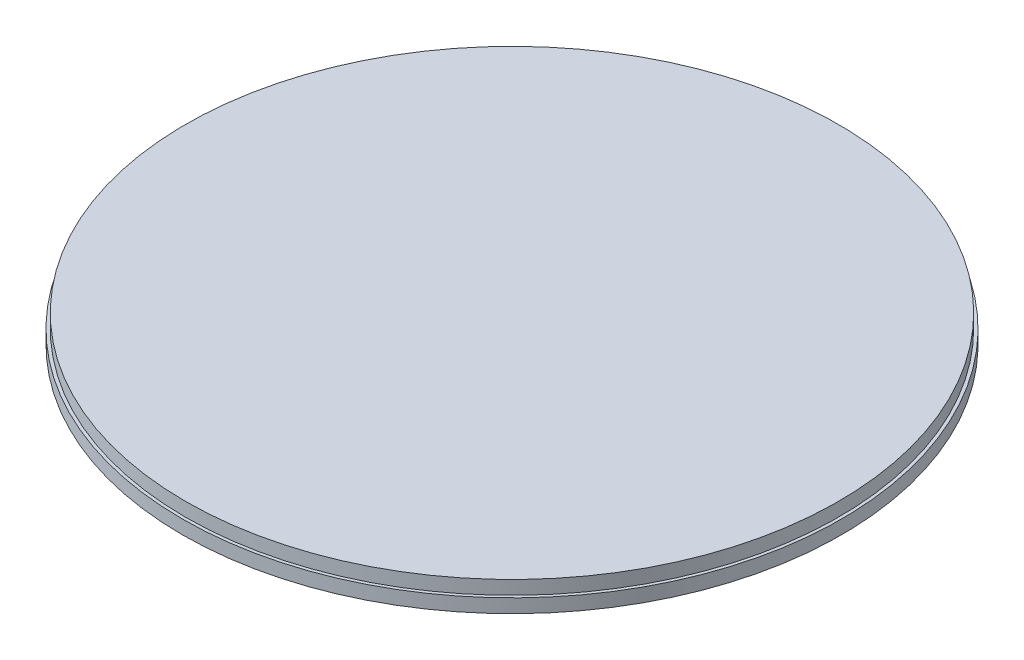
SolidWorks part; units mm, degrees
material "\"G10 fiberglass\""
ref_plane "Front Plane" through (0, 0, 0) normal (0, 0, 1) x (1, 0, 0)
ref_plane "Top Plane" through (0, 0, 0) normal (0, 1, 0) x (1, 0, 0)
ref_plane "Right Plane" through (0, 0, 0) normal (1, 0, 0) x (0, 0, -1)
sketch "Sketch1" plane through (0, 0, 0) normal (0, 1, 0) x (1, 0, 0)
  circle A0 centre (0, 0) radius 76.2
  dimension "D1" = 152.4
extrude "Boss-Extrude1" add sketch "Sketch1" along normal blind 3.175
sketch "Sketch2" plane through (0, 3.175, 0) normal (0, 1, 0) x (1, 0, 0)
  circle A0 centre (0, 0) radius 75.4888
  dimension "D1" = 150.9776
extrude "Boss-Extrude2" add sketch "Sketch2" along normal blind 3.175
equation "\"airframeInnerDiameter\"= 6in"
equation "\"outerDiameter\"= 6.112in"
equation "\"airframeThickness\" = .056in"
equation "\"airframeBulkheadThickness\"= 0.125in"
equation "\"payloadAirframeLength\"= 10in"
equation "\"payloadInnerDiameter\"= 6in - \"airframeThickness\""
equation "\"payloadOuterDiameter\"= \"airframeInnerDiameter\""
equation "\"totalPayloadLength\" = 12in"
equation "\"strutWidth\" = 0.5in"
equation "\"rodDiameter\" = 0.25in"
equation "\"rodSeperation\" = 1.625in"
equation "\"plateThickness\" = .375in"
equation "\"D1@Sketch1\"=\"payloadOuterDiameter\""
equation "\"D1@Boss-Extrude1\"=\"airframeBulkheadThickness\""
equation "\"D1@Sketch2\"=\"payloadInnerDiameter\""
equation "\"D1@Boss-Extrude2\"=\"airframeBulkheadThickness\""
